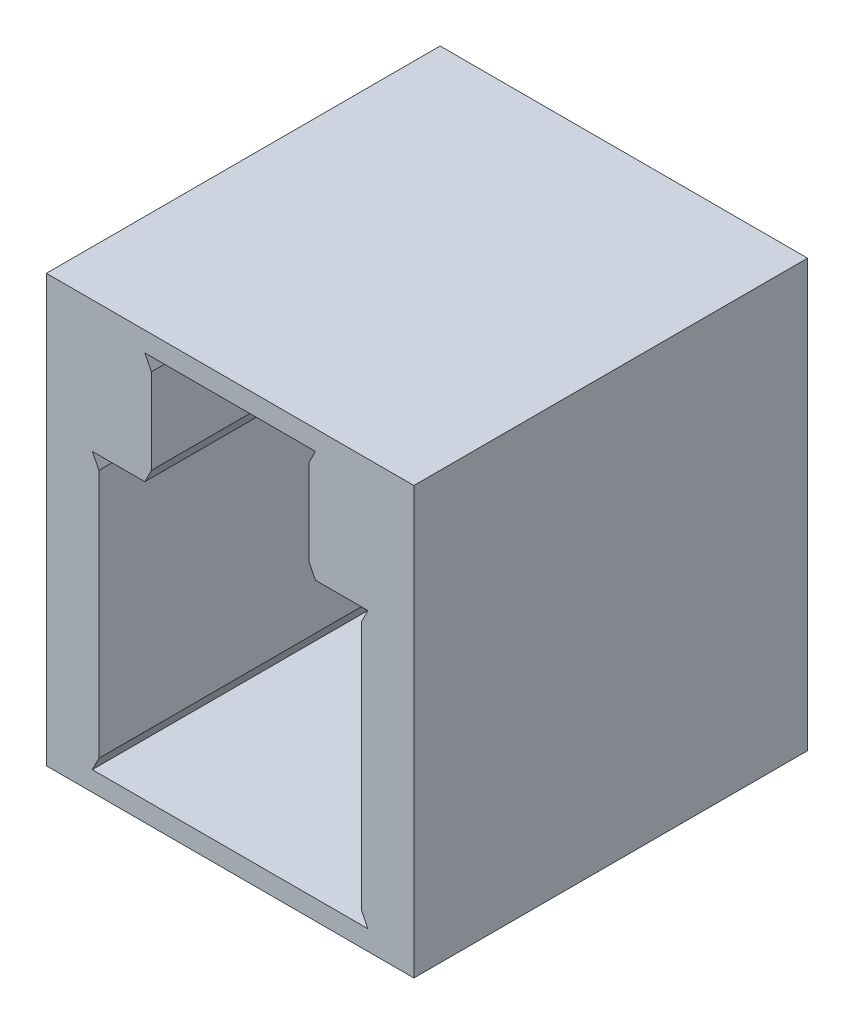
SolidWorks part; units mm, degrees
ref_plane "Front Plane" through (0, 0, 0) normal (0, 0, 1) x (1, 0, 0)
ref_plane "Top Plane" through (0, 0, 0) normal (0, 1, 0) x (1, 0, 0)
ref_plane "Right Plane" through (0, 0, 0) normal (1, 0, 0) x (0, 0, -1)
sketch "Sketch1" plane through (0, 0, 0) normal (0, 1, 0) x (1, 0, 0)
  line L1 (0, 0) -> (28, 0)
  line L2 (0, 0) -> (0, 30)
  line L3 (0, 30) -> (28, 30)
  line L4 (28, 0) -> (28, 30)
  dimension "D1" = 28
  dimension "D2" = 30
extrude "Boss-Extrude1" add sketch "Sketch1" along normal blind 32.5
sketch "Sketch2" plane through (0, 0, 0) normal (0, 0, 1) x (1, 0, 0)
  line L0 (0, 0) -> (28, 0) construction
  line L6 (4, 1.5) -> (24, 1.5)
  line L7 (4, 1.5) -> (4, 22.5)
  line L8 (4, 22.5) -> (24, 22.5)
  line L9 (24, 1.5) -> (24, 22.5)
  line L10 (14, 32.5) -> (14, 1.5) construction
  line L11 (0, 32.5) -> (28, 32.5) construction
  point P10 (14, 22.5)
  dimension "D1" = 20
  dimension "D2" = 21
  dimension "D3" = 1.5
extrude "Cut-Extrude1" cut sketch "Sketch2" against normal through all both and the other way through all
sketch "Sketch3" plane through (0, 0, 0) normal (0, 0, 1) x (1, 0, 0)
  line L0 (4, 22.5) -> (24, 22.5) construction
  line L1 (8, 22.5) -> (20, 22.5)
  line L2 (8, 22.5) -> (8, 31)
  line L3 (8, 31) -> (20, 31)
  line L4 (20, 22.5) -> (20, 31)
  line L5 (14, 22.5) -> (14, 32.5) construction
  line L6 (0, 32.5) -> (28, 32.5) construction
  point P10 (14, 31)
  dimension "D1" = 12
  dimension "D2" = 8.5
extrude "Cut-Extrude2" cut sketch "Sketch3" against normal through all both and the other way through all
sketch "Sketch4" plane through (0, 0, 0) normal (0, 0, 1) x (1, 0, 0)
  line L0 (8, 22.5) -> (8, 23.5)
  line L1 (8, 22.5) -> (8, 31) construction
  line L2 (8, 23.5) -> (7.5, 22.5)
  line L3 (4, 22.5) -> (3.5, 22.5)
  line L4 (7.5, 22.5) -> (8, 22.5)
  line L5 (20, 22.5) -> (20, 23.5)
  line L6 (20, 31) -> (20, 22.5) construction
  line L7 (20, 23.5) -> (20.5, 22.5)
  line L8 (20, 22.5) -> (24, 22.5) construction
  line L9 (20.5, 22.5) -> (20, 22.5)
  line L11 (3.5, 22.5) -> (4, 21.5)
  line L15 (4, 1.5) -> (4, 22.5) construction
  line L17 (4, 21.5) -> (4, 22.5)
  line L19 (8, 31) -> (7.5, 31)
  line L20 (7.5, 31) -> (8, 30)
  line L21 (8, 30) -> (8, 31)
  line L22 (20, 31) -> (20.5, 31)
  line L23 (20.5, 31) -> (20, 30)
  line L24 (20, 30) -> (20, 31)
  line L25 (24, 22.5) -> (24.5, 22.5)
  line L26 (24.5, 22.5) -> (24, 21.5)
  line L27 (24, 22.5) -> (24, 1.5) construction
  line L28 (24, 21.5) -> (24, 22.5)
  line L29 (24, 1.5) -> (24.5, 1.5)
  line L30 (24.5, 1.5) -> (24, 2.5)
  line L31 (24, 2.5) -> (24, 1.5)
  line L32 (4, 1.5) -> (3.5, 1.5)
  line L33 (3.5, 1.5) -> (4, 2.5)
  line L34 (4, 2.5) -> (4, 1.5)
  dimension "D1" = 0.5
  dimension "D2" = 1
  dimension "D3" = 0.5
  dimension "D4" = 1
  dimension "D5" = 0.5
  dimension "D6" = 1
  dimension "D7" = 0.5
  dimension "D8" = 1
  dimension "D9" = 1
  dimension "D10" = 0.5
  dimension "D11" = 0.5
  dimension "D12" = 1
  dimension "D13" = 1
  dimension "D14" = 1
extrude "Cut-Extrude3" cut sketch "Sketch4" against normal through all both and the other way through all
